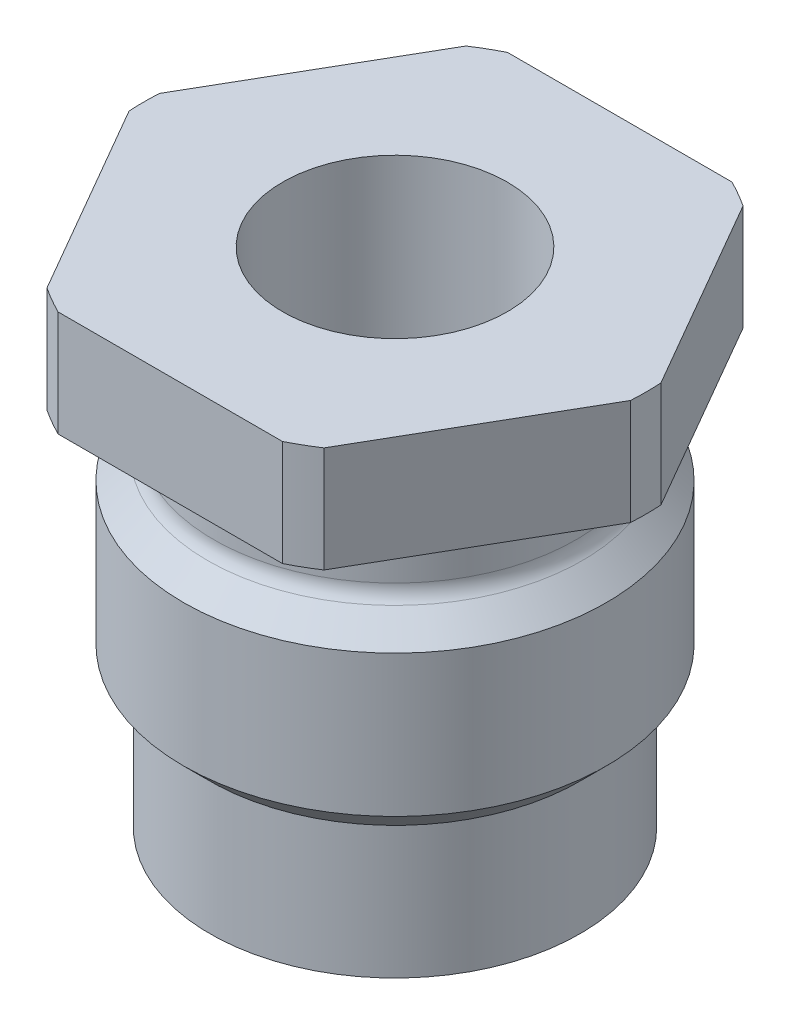
SolidWorks part; units mm, degrees
material "Латунь ЛМц58-2 ГОСТ 15527-2004"
ref_plane "Спереди" through (0, 0, 0) normal (0, 0, 1) x (1, 0, 0)
ref_plane "Сверху" through (0, 0, 0) normal (0, 1, 0) x (1, 0, 0)
ref_plane "Справа" through (0, 0, 0) normal (1, 0, 0) x (0, 0, -1)
other "Табл. исп."
sketch "Эскиз1" plane through (0, 0, 0) normal (0, 0, 1) x (1, 0, 0)
  line L0 (0, 0) -> (0, 20.4488) construction
  line L1 (-4.25, 0) -> (-7, 0)
  line L2 (-7, 0) -> (-7, 5)
  line L3 (-7, 5) -> (-8, 6)
  line L4 (-8, 6) -> (-8, 11.35)
  line L5 (-8, 11.35) -> (-7.0843, 12.2657)
  line L6 (-6.85, 12.8314) -> (-6.85, 14.2)
  line L7 (-7.65, 15) -> (-9.5, 15)
  line L8 (-9.5, 15) -> (-9.5, 19)
  line L9 (-9.5, 19) -> (-4.25, 19)
  line L10 (-4.25, 19) -> (-4.25, 0)
  arc A0 (-7.0843, 12.2657) -> (-6.85, 12.8314) centre (-7.65, 12.8314) ccw
  arc A1 (-6.85, 14.2) -> (-7.65, 15) centre (-7.65, 14.2) ccw
  point P15 (-6.85, 12.5)
  point P18 (-6.85, 15)
  dimension "D11" = 0.8
  dimension "D1" = 8.5
  dimension "D2" = 14
  dimension "D3" = 16
  dimension "D4" = 45
  dimension "D5" = 13.7
  dimension "D6" = 19
  dimension "D7" = 5
  dimension "D8" = 4
  dimension "D9" = 2.5
  dimension "D10" = 19
revolve "Повернуть1" add sketch "Эскиз1" angle 360 about L0
cosmetic thread "Условное изображение резьбы1" parameters "D1"=5, "D2"=13.797
sketch "Эскиз2" plane through (0, 19, 0) normal (0, 1, 0) x (1, 0, 0)
  line L1 (9.815, 0) -> (4.9075, 8.5)
  line L2 (4.9075, 8.5) -> (-4.9075, 8.5)
  line L3 (-4.9075, 8.5) -> (-9.815, 0)
  line L4 (-9.815, 0) -> (-4.9075, -8.5)
  line L5 (-4.9075, -8.5) -> (4.9075, -8.5)
  line L6 (4.9075, -8.5) -> (9.815, 0)
  circle A0 centre (0, 0) radius 8.5 construction
  dimension "D1" = 17
extrude "Вырез-Вытянуть1" cut sketch "Эскиз2" against normal through all flip side to cut
